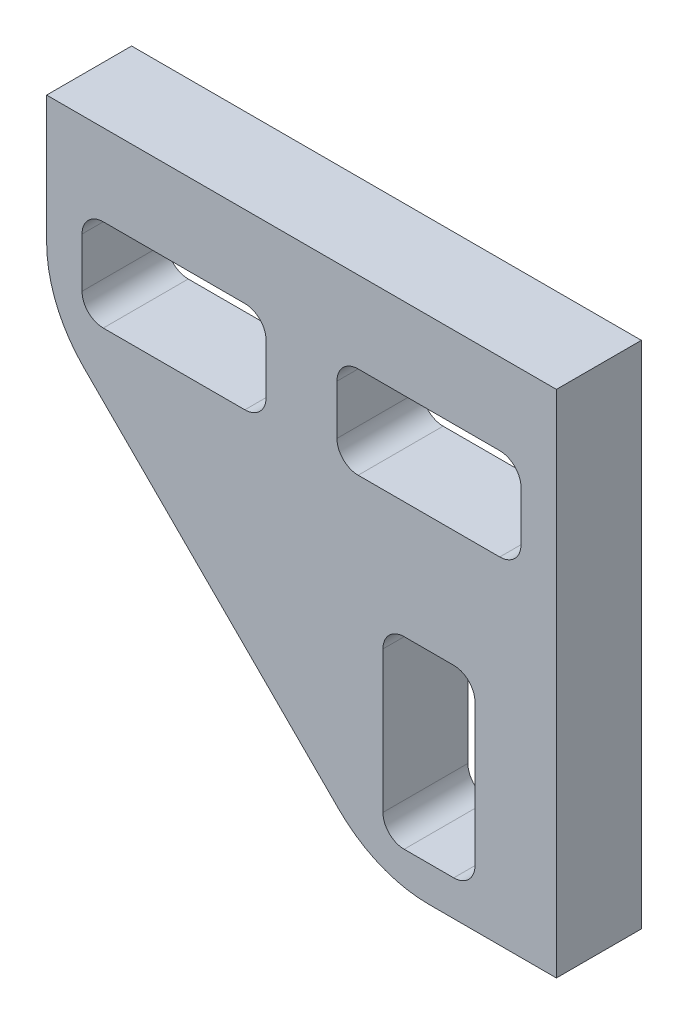
SolidWorks part; units mm, degrees
ref_plane "Alzado" through (0, 0, 0) normal (0, 0, 1) x (1, 0, 0)
ref_plane "Planta" through (0, 0, 0) normal (0, 1, 0) x (1, 0, 0)
ref_plane "Vista lateral" through (0, 0, 0) normal (1, 0, 0) x (0, 0, -1)
sketch "Model" plane through (0, 0, 0) normal (0, 0, 1) x (1, 0, 0)
  line L0 (149.3421, 211.824) -> (158.3421, 211.824)
  line L1 (162.8421, 198.324) -> (162.8421, 211.824)
  line L2 (156.7171, 195.824) -> (156.7171, 200.824)
  line L3 (157.4671, 201.574) -> (159.2171, 201.574)
  line L4 (159.9671, 200.824) -> (159.9671, 195.824)
  line L5 (159.2171, 195.074) -> (157.4671, 195.074)
  line L6 (151.8421, 205.699) -> (146.8421, 205.699)
  line L7 (146.0921, 206.449) -> (146.0921, 208.199)
  line L8 (146.8421, 208.949) -> (151.8421, 208.949)
  line L9 (152.5921, 208.199) -> (152.5921, 206.449)
  line L10 (160.8421, 205.699) -> (155.8421, 205.699)
  line L11 (155.0921, 206.449) -> (155.0921, 208.199)
  line L12 (155.8421, 208.949) -> (160.8421, 208.949)
  line L13 (161.5921, 208.199) -> (161.5921, 206.449)
  line L14 (149.3421, 211.824) -> (144.8421, 211.824)
  line L15 (158.3421, 211.824) -> (162.8421, 211.824)
  line L16 (144.8421, 207.324) -> (144.8421, 211.824)
  line L17 (162.8421, 198.324) -> (162.8421, 193.824)
  line L18 (158.3421, 193.824) -> (162.8421, 193.824)
  line L19 (146.1602, 204.142) -> (155.1602, 195.142)
  arc A0 (144.8421, 207.324) -> (146.1602, 204.142) centre (149.3421, 207.324) ccw
  arc A1 (155.1602, 195.142) -> (158.3421, 193.824) centre (158.3421, 198.324) ccw
  arc A2 (157.4671, 201.574) -> (156.7171, 200.824) centre (157.4671, 200.824) ccw
  arc A3 (159.9671, 200.824) -> (159.2171, 201.574) centre (159.2171, 200.824) ccw
  arc A4 (159.2171, 195.074) -> (159.9671, 195.824) centre (159.2171, 195.824) ccw
  arc A5 (156.7171, 195.824) -> (157.4671, 195.074) centre (157.4671, 195.824) ccw
  arc A6 (146.0921, 206.449) -> (146.8421, 205.699) centre (146.8421, 206.449) ccw
  arc A7 (146.8421, 208.949) -> (146.0921, 208.199) centre (146.8421, 208.199) ccw
  arc A8 (152.5921, 208.199) -> (151.8421, 208.949) centre (151.8421, 208.199) ccw
  arc A9 (151.8421, 205.699) -> (152.5921, 206.449) centre (151.8421, 206.449) ccw
  arc A10 (155.0921, 206.449) -> (155.8421, 205.699) centre (155.8421, 206.449) ccw
  arc A11 (155.8421, 208.949) -> (155.0921, 208.199) centre (155.8421, 208.199) ccw
  arc A12 (161.5921, 208.199) -> (160.8421, 208.949) centre (160.8421, 208.199) ccw
  arc A13 (160.8421, 205.699) -> (161.5921, 206.449) centre (160.8421, 206.449) ccw
extrude "Saliente-Extruir1" add sketch "Model" along normal blind 3
